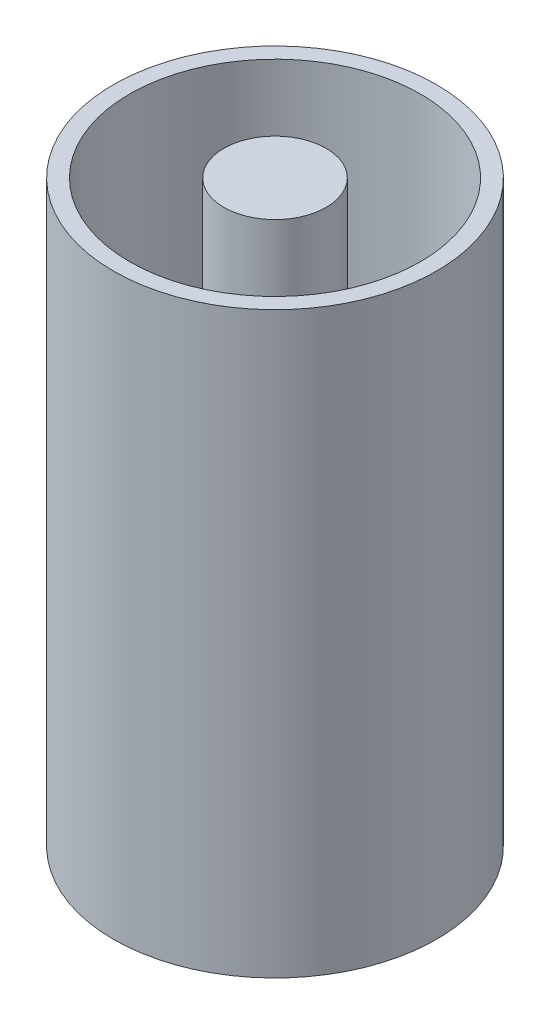
SolidWorks part; units mm, degrees
ref_plane "Front Plane" through (0, 0, 0) normal (0, 0, 1) x (1, 0, 0)
ref_plane "Top Plane" through (0, 0, 0) normal (0, 1, 0) x (1, 0, 0)
ref_plane "Right Plane" through (0, 0, 0) normal (1, 0, 0) x (0, 0, -1)
sketch "Sketch1" plane through (0, 0, 0) normal (0, 1, 0) x (1, 0, 0)
  circle A0 centre (0, 0) radius 20
  circle A1 centre (0, 0) radius 36
  circle A2 centre (0, 0) radius 40
  dimension "D1" = 40
  dimension "D2" = 72
  dimension "D3" = 80
extrude "Boss-Extrude1" add sketch "Sketch1" along normal blind 10
sketch "Sketch2" plane through (0, 0, 0) normal (0, 0, 1) x (1, 0, 0)
  line L0 (0, 85.4193) -> (0, -73.7814) construction
sketch "Sketch3" plane through (0, 0, 0) normal (1, 0, 0) x (0, 0, -1)
  line L0 (-40, 0) -> (40, 0) construction
  line L1 (-36, 10) -> (-20, 10) construction
  line L2 (-36, 10) -> (-36, 0) construction
  line L3 (-36, 0) -> (-20, 0) construction
  line L4 (-20, 10) -> (-20, 0) construction
  line L5 (20, 10) -> (-20, 10) construction
  line L6 (-20, 10) -> (-20, 0) construction
sketch "Sketch4" plane through (0, 0, 0) normal (1, 0, 0) x (0, 0, -1)
  line L0 (2.0974, 0) -> (4.0314, 10)
  line L1 (-40, 0) -> (40, 0) construction
  line L2 (40, 10) -> (-40, 10) construction
  line L3 (3.3811, 0) -> (5.3151, 10)
  line L4 (5.3151, 10) -> (4.0314, 10)
  line L5 (2.0974, 0) -> (3.3811, 0)
extrude "Boss-Extrude2" add sketch "Sketch4" against normal up to next and the other way up to next from offset 30
pattern_circular "CirPattern1" count 12 over 360 about axis through (0, 0, 0) along (0, 1, 0) of "Boss-Extrude2"
sketch "Sketch5" plane through (0, 10, 0) normal (0, 1, 0) x (1, 0, 0)
  line L0 (-18.685, 0) -> (17.5222, 0) construction
  line L1 (0, 15.5239) -> (0, -14.8175) construction
  circle A0 centre (-14.887, 0) radius 1.7357
  circle A1 centre (-7.4435, 12.8925) radius 1.7357
  circle A2 centre (7.4435, 12.8925) radius 1.7357
  circle A3 centre (14.887, 0) radius 1.7357
  circle A4 centre (7.4435, -12.8925) radius 1.7357
  circle A5 centre (-7.4435, -12.8925) radius 1.7357
  point P20 (0, 0)
  dimension "D1" = 6
extrude "Boss-Extrude3" add sketch "Sketch5" along normal blind 5
scale "Scale1" scale about origin uniform scaling yes scale factor 0.75
sketch "Sketch7" plane through (0, 7.5, 0) normal (0, 1, 0) x (1, 0, 0)
  circle A0 centre (0, 0) radius 9.5
  dimension "D1" = 19
sketch "Sketch6" plane through (0, 7.5, 0) normal (0, 1, 0) x (1, 0, 0)
  circle A0 centre (0, 0) radius 30
  circle A1 centre (0, 0) radius 27
extrude "Boss-Extrude4" add sketch "Sketch6" along normal blind 100
extrude "Boss-Extrude5" add sketch "Sketch7" along normal blind 100
equation "\"D1@Sketch1\"= \"D3@Sketch1\" / 2"
